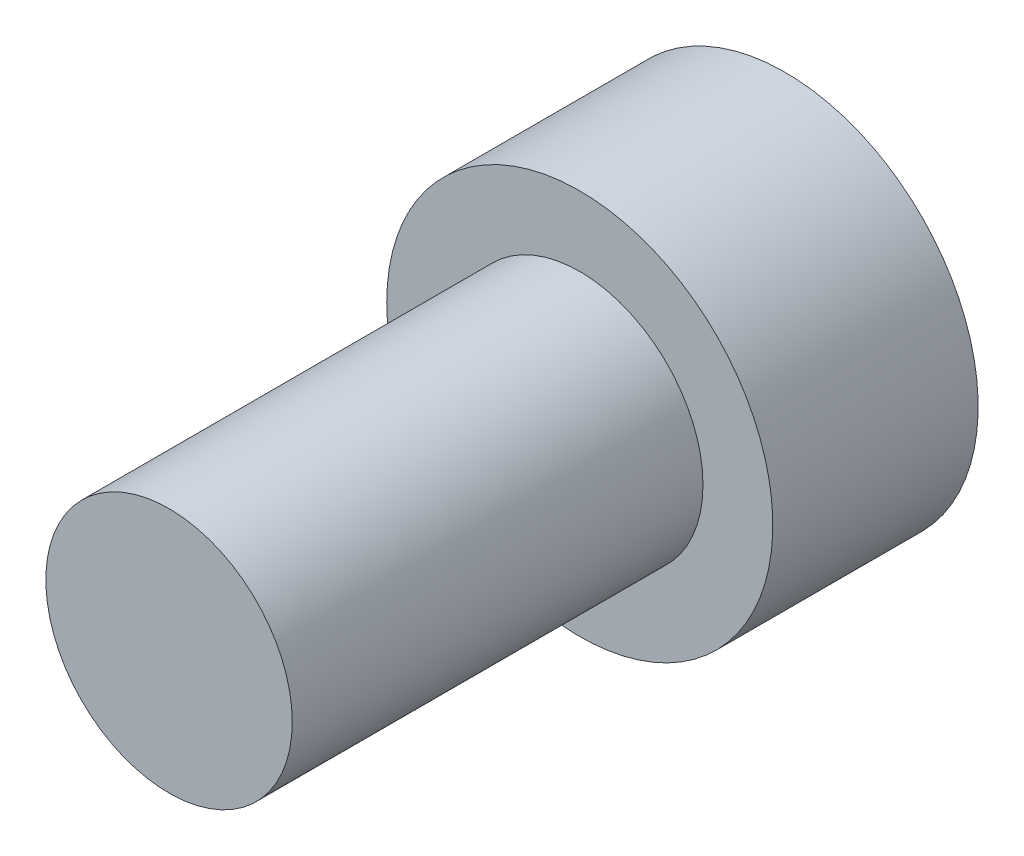
SolidWorks part; units mm, degrees
ref_plane "Front Plane" through (0, 0, 0) normal (0, 0, 1) x (1, 0, 0)
ref_plane "Top Plane" through (0, 0, 0) normal (0, 1, 0) x (1, 0, 0)
ref_plane "Right Plane" through (0, 0, 0) normal (1, 0, 0) x (0, 0, -1)
sketch "Sketch1" plane through (0, 0, 0) normal (0, 0, 1) x (1, 0, 0)
  circle A0 centre (0, 0) radius 1.5
  dimension "D1" = 3
extrude "Boss-Extrude1" add sketch "Sketch1" along normal blind 5
sketch "Sketch2" plane through (0, 0, 0) normal (0, 0, -1) x (-1, 0, 0)
  circle A0 centre (0, 0) radius 2.35
  dimension "D1" = 4.7
extrude "Boss-Extrude2" add sketch "Sketch2" along normal blind 2.5
